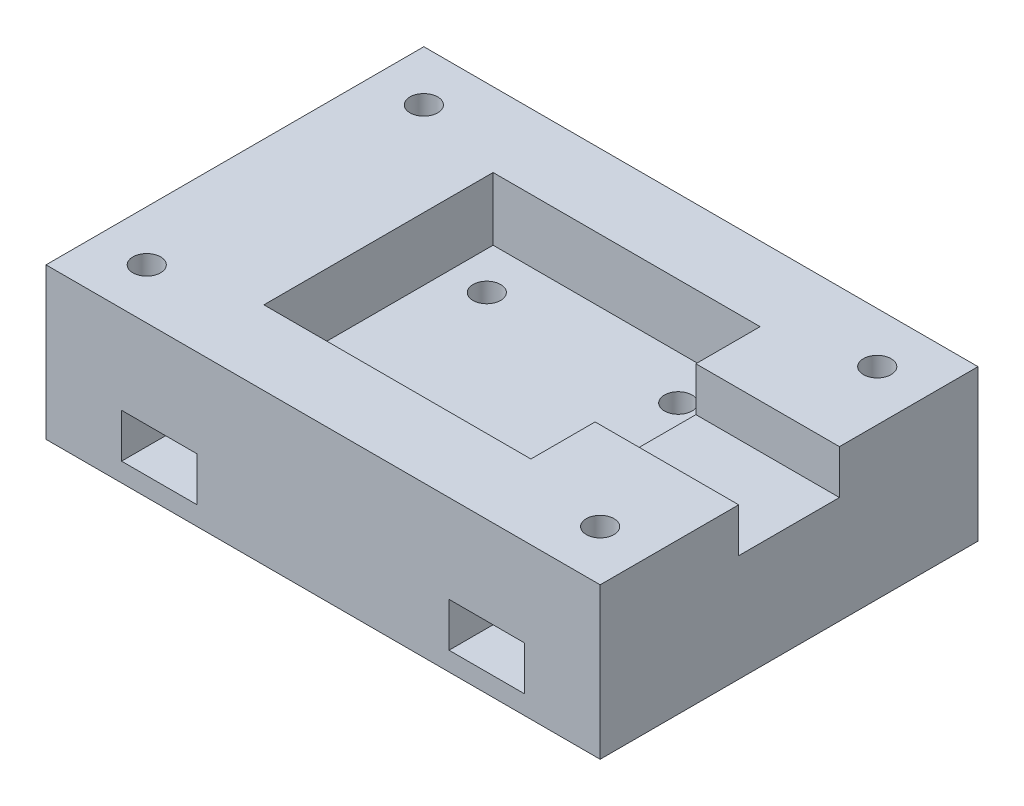
SolidWorks part; units mm, degrees
ref_plane "Front Plane" through (0, 0, 0) normal (0, 0, 1) x (1, 0, 0)
ref_plane "Top Plane" through (0, 0, 0) normal (0, 1, 0) x (1, 0, 0)
ref_plane "Right Plane" through (0, 0, 0) normal (1, 0, 0) x (0, 0, -1)
sketch "Sketch1" plane through (0, 0, 0) normal (0, 1, 0) x (1, 0, 0)
  line L1 (-22, -15) -> (22, -15)
  line L2 (-22, -15) -> (-22, 15)
  line L3 (-22, 15) -> (22, 15)
  line L4 (22, -15) -> (22, 15)
  line L5 (-22, -15) -> (22, 15) construction
  line L6 (-22, 15) -> (22, -15) construction
  point P0 (0, 0)
  dimension "D1" = 44
  dimension "D2" = 30
extrude "Pod Body" add sketch "Sketch1" along normal blind 12
ref_plane "Pod Top" through (0, 12, 0) normal (0, 1, 0) x (1, 0, 0)
sketch "Sketch2" plane through (0, 12, 0) normal (0, 1, 0) x (1, 0, 0)
  line L1 (-10.6, -9.1) -> (10.6, -9.1)
  line L2 (-10.6, -9.1) -> (-10.6, 9.1)
  line L3 (-10.6, 9.1) -> (10.6, 9.1)
  line L4 (10.6, -9.1) -> (10.6, 9.1)
  line L5 (-10.6, -9.1) -> (10.6, 9.1) construction
  line L6 (-10.6, 9.1) -> (10.6, -9.1) construction
  point P0 (0, 0)
  dimension "D1" = 21.2
  dimension "D2" = 18.2
extrude "Board Pocket" cut sketch "Sketch2" against normal blind 5
sketch "Sketch3" plane through (0, 12, 0) normal (0, 1, 0) x (1, 0, 0)
  circle A0 centre (-7.6, 5.6) radius 1.1
  circle A1 centre (7.6, 5.6) radius 1.1
extrude "Board Pilot Holes" cut sketch "Sketch3" against normal blind 9
sketch "Sketch4" plane through (0, 12, 0) normal (0, 1, 0) x (1, 0, 0)
  circle A0 centre (-18, -11) radius 1.1
  circle A1 centre (-18, 11) radius 1.1
  circle A2 centre (18, -11) radius 1.1
  circle A3 centre (18, 11) radius 1.1
extrude "Lid Pilot Holes" cut sketch "Sketch4" against normal blind 8
sketch "Sketch5" plane through (0, 12, 0) normal (0, 1, 0) x (1, 0, 0)
  line L1 (10.35, -4) -> (23, -4)
  line L2 (10.35, -4) -> (10.35, 4)
  line L3 (10.35, 4) -> (23, 4)
  line L4 (23, -4) -> (23, 4)
extrude "Cable Exit" cut sketch "Sketch5" against normal blind 3.5
sketch "Sketch7" plane through (0, 0, 0) normal (0, 0, 1) x (1, 0, 0)
  line L0 (-12, 5) -> (-6, 5) construction
  line L1 (-16, 1.5) -> (-10, 1.5)
  line L2 (-16, 1.5) -> (-16, 5)
  line L3 (-16, 5) -> (-10, 5)
  line L4 (-10, 1.5) -> (-10, 5)
  line L5 (6, 1.5) -> (12, 1.5) construction
  line L6 (10, 1.5) -> (16, 1.5)
  line L7 (10, 1.5) -> (10, 5)
  line L8 (10, 5) -> (16, 5)
  line L9 (16, 1.5) -> (16, 5)
extrude "Strap Slots" cut sketch "Sketch7" against normal through all and the other way through all
equation "\"PodL\"= 44.0"
equation "\"PodW\"= 30.0"
equation "\"PodH\"= 12.0"
equation "\"BoardL\" = 20.0"
equation "\"BoardW\" = 17.0"
equation "\"Clear\"= 0.6"
equation "\"PocketD\"= 5.0"
equation "\"D1@Sketch1\" = \"PodL\""
equation "\"D2@Sketch1\" = \"PodW\""
equation "\"HoleSpacing\"= 15.2"
equation "\"HoleOffset\"= 5.6"
equation "\"PilotD\"= 2.2"
equation "\"FloorHoleD\"= 4.0"
equation "\"LidInset\"= 4.0"
equation "\"StrapX\"= 13.0"
equation "\"StrapW\"= 6.0"
equation "\"StrapT\"= 3.5"
equation "\"StrapZ0\"= 1.5"
equation "\"CableW\"= 8.0"
equation "\"D1@Pod Top\" = \"PodH\""
equation "\"D1@Sketch2\" = \"BoardL\" + 2 * \"Clear\""
equation "\"D2@Sketch2\" = \"BoardW\" + 2 * \"Clear\""
equation "\"D1@Board Pocket\" = \"PocketD\""
equation "\"D1@Board Pilot Holes\" = \"PocketD\" + \"FloorHoleD\""
